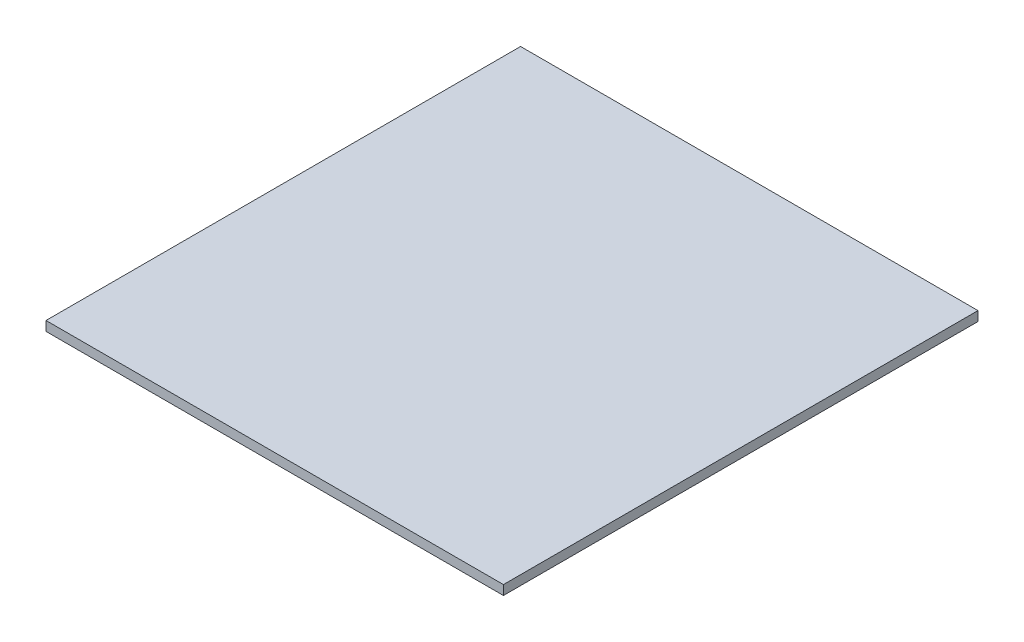
SolidWorks part; units mm, degrees
ref_plane "Front Plane" through (0, 0, 0) normal (0, 0, 1) x (1, 0, 0)
ref_plane "Top Plane" through (0, 0, 0) normal (0, 1, 0) x (1, 0, 0)
ref_plane "Right Plane" through (0, 0, 0) normal (1, 0, 0) x (0, 0, -1)
sketch "Sketch2" plane through (0, 0, 0) normal (0, 0, 1) x (1, 0, 0)
  line L1 (0, 0) -> (144.58, 0)
  line L2 (0, 0) -> (0, -3)
  line L3 (0, -3) -> (144.58, -3)
  line L4 (144.58, 0) -> (144.58, -3)
  dimension "D1" = 3
  dimension "D2" = 144.58
extrude "Boss-Extrude1" add sketch "Sketch2" along normal blind 150
